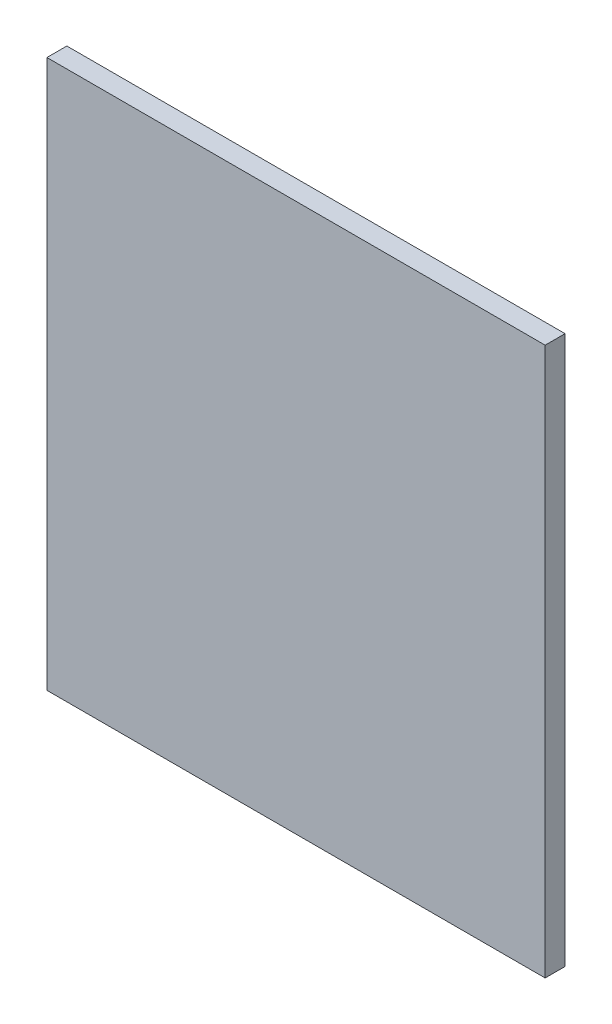
SolidWorks part; units mm, degrees
ref_plane "Front Plane" through (0, 0, 0) normal (0, 0, 1) x (1, 0, 0)
ref_plane "Top Plane" through (0, 0, 0) normal (0, 1, 0) x (1, 0, 0)
ref_plane "Right Plane" through (0, 0, 0) normal (1, 0, 0) x (0, 0, -1)
sketch "Sketch1" plane through (0, 0, 0) normal (0, 0, 1) x (1, 0, 0)
  line L1 (0, 0) -> (50, 0)
  line L2 (0, 0) -> (0, 55)
  line L3 (0, 55) -> (50, 55)
  line L4 (50, 0) -> (50, 55)
  dimension "D1" = 50
  dimension "D2" = 55
extrude "Profile" add sketch "Sketch1" along normal blind 2
equation "\"Profile_Depth\"= 2mm"
equation "\"D1@Profile\" = \"Profile_Depth\""
equation "\"Profile_Sketch_1\"= 50mm"
equation "\"D1@Sketch1\" = \"Profile_Sketch_1\""
equation "\"Profile_Sketch_2\"= 55mm"
equation "\"D2@Sketch1\" = \"Profile_Sketch_2\""
equation "\"EnvelopeWidth\"= 50mm"
equation "\"EnvelopeHeight\"= 55mm"
